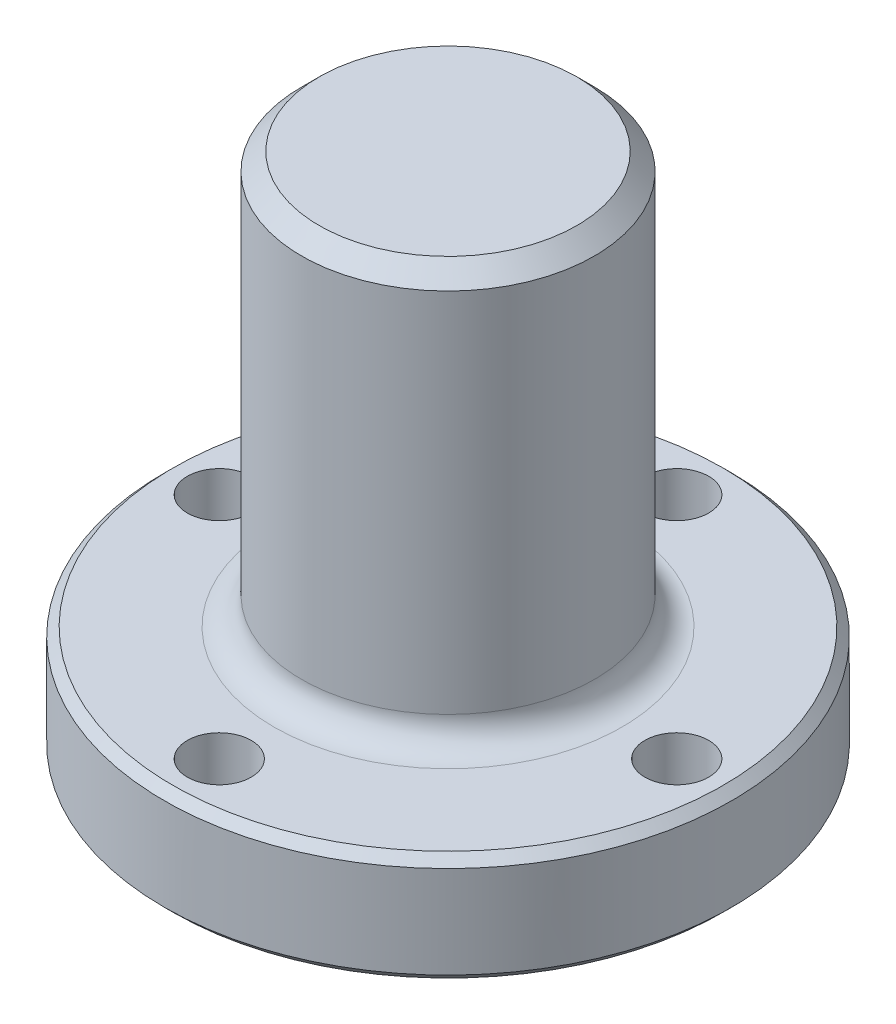
SolidWorks part; units mm, degrees
ref_plane "Front Plane" through (0, 0, 0) normal (1, 0, 0) x (0, 1, 0)
ref_plane "Top Plane" through (0, 0, 0) normal (0, 0, 1) x (0, 1, 0)
ref_plane "Right Plane" through (0, 0, 0) normal (0, 1, 0) x (-1, 0, 0)
sketch "Sketch1" plane through (0, 0, 0) normal (0, 0, 1) x (0, 1, 0)
  line L0 (-25.0317, 0) -> (-25.0317, 8.7122)
  line L1 (-25.0317, 8.7122) -> (-20.2057, 8.7122)
  line L2 (-20.2057, 8.7122) -> (-20.2057, 24.6126)
  line L3 (-20.2057, 24.6126) -> (-10.6807, 24.6126)
  line L4 (-10.6807, 24.6126) -> (-10.6807, 12.7)
  line L5 (-10.6807, 12.7) -> (25.0317, 12.7)
  line L6 (25.0317, 12.7) -> (25.0317, 0)
  line L7 (25.0317, 0) -> (-25.0317, 0)
  line L8 (-50.4317, 0) -> (50.4317, 0) construction
  dimension "D1" = 35.7124
  dimension "D2" = 45.2374
  dimension "D3" = 50.0634
  dimension "D4" = 11.9126
  dimension "D5" = 15.9004
  dimension "D6" = 24.6126
revolve "Revolve1" add sketch "Sketch1" angle 360 about L8
fillet "Fillet1" radius 2.3876 1 edges at (0, -10.6807, -12.7)
chamfer "Chamfer1" distance 0.762 angle 45 3 edges at (0, -10.6807, -24.6126) (0, -20.2057, -24.6126) (0, -25.0317, -8.7122)
chamfer "Chamfer2" distance 1.524 angle 45 1 edges at (0, 25.0317, -12.7)
sketch "Sketch2" plane through (0, 0, 0) normal (0, 1, 0) x (-1, 0, 0)
  circle A0 centre (19.8374, 0) radius 2.7686
  circle A1 centre (0, 19.8374) radius 2.7686
  circle A2 centre (-19.8374, 0) radius 2.7686
  circle A3 centre (0, -19.8374) radius 2.7686
  dimension "D1" = 5.5372
  dimension "D2" = 5.5372
  dimension "D3" = 5.5372
  dimension "D4" = 5.5372
  dimension "D5" = 19.8374
  dimension "D6" = 19.8374
  dimension "D7" = 39.6748
  dimension "D8" = 19.8374
  dimension "D9" = 19.8374
  dimension "D10" = 39.6748
extrude "Cut-Extrude2" cut sketch "Sketch2" against normal blind 10.6807 from offset 10.6807
